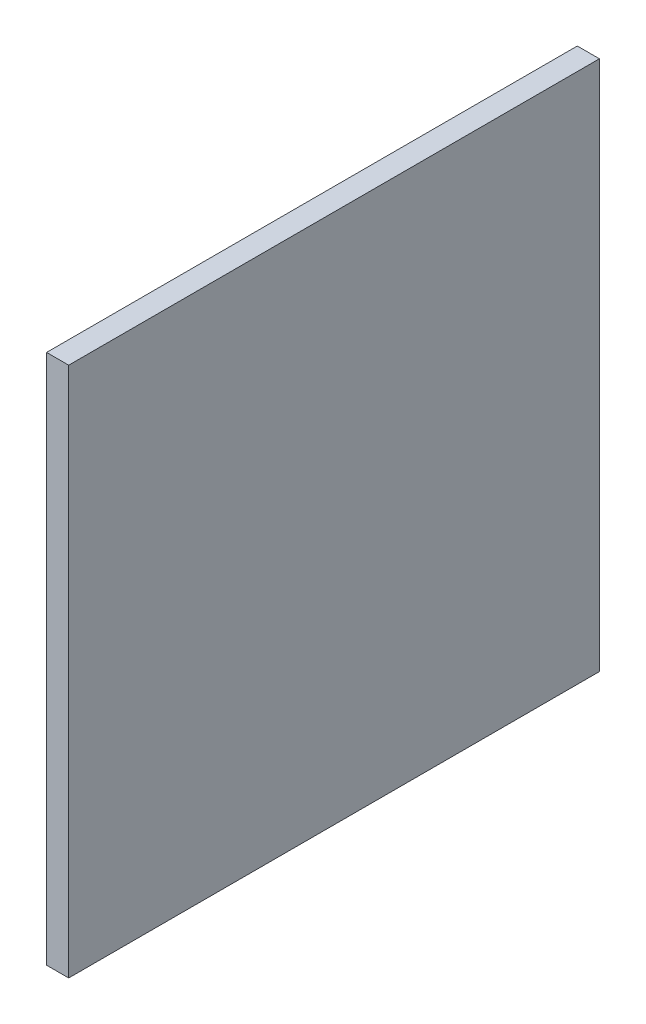
SolidWorks part; units mm, degrees
ref_plane "前视基准面" through (0, 0, 0) normal (0, 0, 1) x (1, 0, 0)
ref_plane "上视基准面" through (0, 0, 0) normal (0, 1, 0) x (1, 0, 0)
ref_plane "右视基准面" through (0, 0, 0) normal (1, 0, 0) x (0, 0, -1)
sketch "草图8" plane through (0, 0, 0) normal (0, 0, 1) x (1, 0, 0)
  line L1 (-1.25, -30) -> (1.25, -30)
  line L2 (-1.25, -30) -> (-1.25, 30)
  line L3 (-1.25, 30) -> (1.25, 30)
  line L4 (1.25, -30) -> (1.25, 30)
  line L5 (-1.25, -30) -> (1.25, 30) construction
  line L6 (-1.25, 30) -> (1.25, -30) construction
  point P0 (0, 0)
  dimension "D1" = 60
  dimension "D2" = 2.5
extrude "凸台-拉伸4" add sketch "草图8" along normal mid plane 60
sketch "草图9" plane through (-1.25, 0, 0) normal (-1, 0, 0) x (0, 0, 1)
  line L0 (30, 30) -> (-30, 30) construction
  line L1 (17.1713, 30) -> (20.1713, 30)
  line L2 (17.1713, 30) -> (17.1713, 11.9321)
  line L3 (17.1713, 11.9321) -> (20.1713, 11.9321)
  line L4 (20.1713, 30) -> (20.1713, 11.9321)
  dimension "D1" = 3
